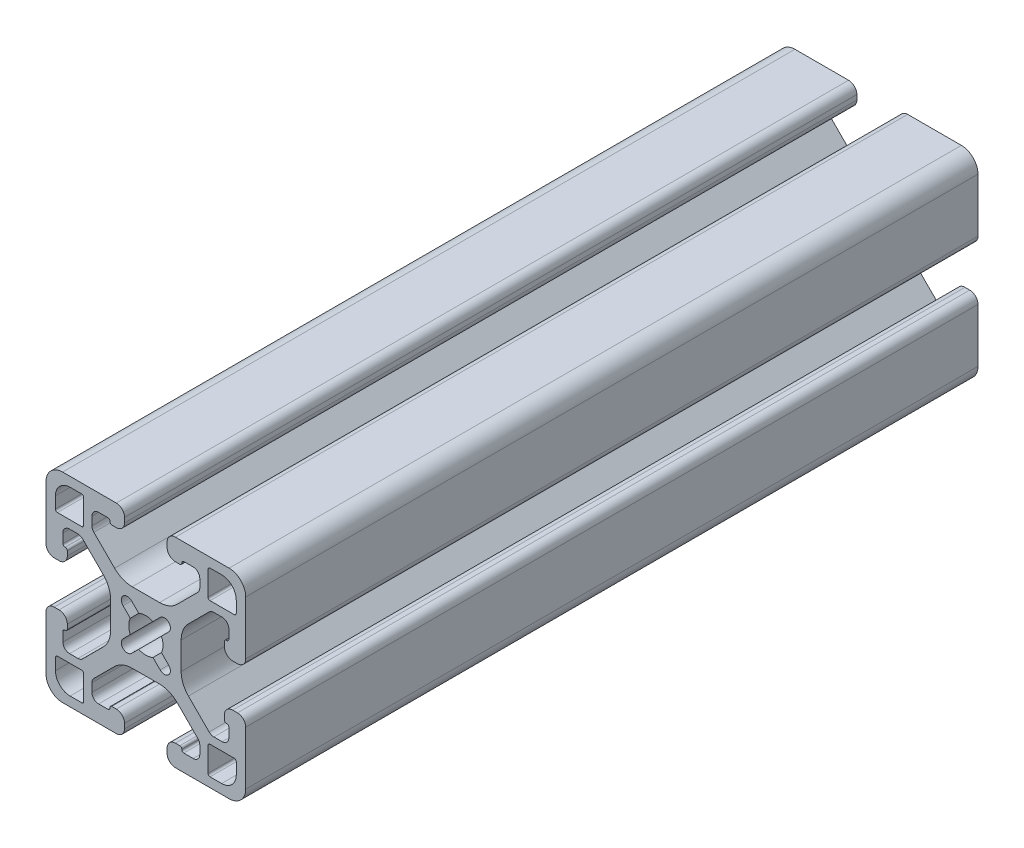
SolidWorks part; units mm, degrees
ref_plane "Front Plane" through (0, 0, 0) normal (0, 0, 1) x (1, 0, 0)
ref_plane "Top Plane" through (0, 0, 0) normal (0, 1, 0) x (1, 0, 0)
ref_plane "Right Plane" through (0, 0, 0) normal (1, 0, 0) x (0, 0, -1)
sketch "Sketch1" plane through (0, 0, 0) normal (0, 0, 1) x (1, 0, 0)
  line L0 (-66.7042, -2.4885) -> (-65.3338, -1.1181)
  line L1 (-65.3338, 1.5948) -> (-66.7042, 2.9652)
  line L2 (-65.0878, 4.5817) -> (-63.7174, 3.2113)
  line L3 (-61.0045, 3.2113) -> (-59.7212, 4.484)
  line L4 (-58.1153, 2.8781) -> (-59.3881, 1.5948)
  line L5 (-59.3881, -1.1181) -> (-58.0176, -2.4885)
  line L6 (-59.6341, -4.1049) -> (-61.0045, -2.7345)
  line L7 (-63.7174, -2.7345) -> (-65.0878, -4.1049)
  line L8 (-79.6075, 12.4812) -> (-79.6075, 14.691)
  line L9 (-76.8135, 17.485) -> (-74.6037, 17.485)
  line L10 (-74.2227, 17.104) -> (-74.2227, 12.4812)
  line L11 (-74.6037, 12.1002) -> (-79.2265, 12.1002)
  line L12 (-74.6037, -17.0082) -> (-76.8135, -17.0082)
  line L13 (-79.6075, -14.2142) -> (-79.6075, -12.0044)
  line L14 (-79.2265, -11.6234) -> (-74.6037, -11.6234)
  line L15 (-74.2227, -12.0044) -> (-74.2227, -16.6272)
  line L16 (-45.1143, -12.0044) -> (-45.1143, -14.2142)
  line L17 (-47.9083, -17.0082) -> (-50.1181, -17.0082)
  line L18 (-50.4991, -16.6272) -> (-50.4991, -12.0044)
  line L19 (-50.1181, -11.6234) -> (-45.4953, -11.6234)
  line L20 (-50.1181, 17.485) -> (-47.9083, 17.485)
  line L21 (-45.1143, 14.691) -> (-45.1143, 12.4812)
  line L22 (-45.4953, 12.1002) -> (-50.1181, 12.1002)
  line L23 (-50.4991, 12.4812) -> (-50.4991, 17.104)
  line L24 (-46.5368, -7.0006) -> (-46.5368, -8.7746)
  line L25 (-47.8067, -10.0486) -> (-49.3926, -10.0486)
  line L26 (-50.2907, -9.6767) -> (-54.2388, -5.7286)
  line L27 (-55.6299, -2.3699) -> (-55.6299, 2.8467)
  line L28 (-54.2388, 6.2053) -> (-50.2907, 10.1534)
  line L29 (-49.3926, 10.5254) -> (-47.8067, 10.5254)
  line L30 (-46.5368, 9.2513) -> (-46.5368, 7.4774)
  line L31 (-46.9178, 7.0964) -> (-46.994, 7.0964)
  line L32 (-47.375, 6.7154) -> (-47.3749, 5.8772)
  line L33 (-45.8001, 4.3024) -> (-44.8857, 4.3024)
  line L34 (-43.3109, 5.8772) -> (-43.3109, 16.1134)
  line L35 (-46.4859, 19.2884) -> (-56.7221, 19.2884)
  line L36 (-58.2969, 17.7136) -> (-58.2969, 16.7992)
  line L37 (-56.7222, 15.2244) -> (-55.884, 15.2244)
  line L38 (-55.503, 15.6054) -> (-55.503, 15.6816)
  line L39 (-55.122, 16.0626) -> (-53.348, 16.0626)
  line L40 (-52.0739, 14.7926) -> (-52.0739, 13.2067)
  line L41 (-52.4459, 12.3087) -> (-56.394, 8.3606)
  line L42 (-59.7526, 6.9694) -> (-64.9693, 6.9694)
  line L43 (-68.3279, 8.3606) -> (-72.276, 12.3087)
  line L44 (-72.6479, 13.2067) -> (-72.6479, 14.7926)
  line L45 (-71.3739, 16.0626) -> (-69.5999, 16.0626)
  line L46 (-69.2189, 15.6816) -> (-69.2189, 15.6054)
  line L47 (-68.8379, 15.2244) -> (-67.9997, 15.2244)
  line L48 (-66.4249, 16.7992) -> (-66.4249, 17.7136)
  line L49 (-67.9997, 19.2884) -> (-78.2359, 19.2884)
  line L50 (-81.4109, 16.1134) -> (-81.4109, 5.8772)
  line L51 (-79.8361, 4.3024) -> (-78.9217, 4.3024)
  line L52 (-77.3469, 5.8772) -> (-77.3469, 6.7154)
  line L53 (-77.7279, 7.0964) -> (-77.8041, 7.0964)
  line L54 (-78.1851, 7.4774) -> (-78.1851, 9.2513)
  line L55 (-76.9151, 10.5254) -> (-75.3293, 10.5254)
  line L56 (-74.4312, 10.1534) -> (-70.4831, 6.2053)
  line L57 (-69.0919, 2.8467) -> (-69.0919, -2.3699)
  line L58 (-70.4831, -5.7286) -> (-74.4312, -9.6767)
  line L59 (-75.3293, -10.0486) -> (-76.9151, -10.0486)
  line L60 (-78.1851, -8.7746) -> (-78.1851, -7.0006)
  line L61 (-77.8041, -6.6196) -> (-77.7279, -6.6196)
  line L62 (-77.3469, -6.2386) -> (-77.3469, -5.4004)
  line L63 (-78.9217, -3.8256) -> (-79.8361, -3.8256)
  line L64 (-81.4109, -5.4004) -> (-81.4109, -15.6366)
  line L65 (-78.2359, -18.8116) -> (-67.9997, -18.8116)
  line L66 (-66.4249, -17.2368) -> (-66.4249, -16.3224)
  line L67 (-67.9997, -14.7476) -> (-68.8379, -14.7476)
  line L68 (-69.2189, -15.1286) -> (-69.2189, -15.2048)
  line L69 (-69.5999, -15.5858) -> (-71.3739, -15.5858)
  line L70 (-72.6479, -14.3158) -> (-72.6479, -12.7299)
  line L71 (-72.276, -11.8319) -> (-68.3279, -7.8838)
  line L72 (-64.9693, -6.4926) -> (-59.7526, -6.4926)
  line L73 (-56.394, -7.8838) -> (-52.4459, -11.8319)
  line L74 (-52.0739, -12.7299) -> (-52.0739, -14.3158)
  line L75 (-53.348, -15.5858) -> (-55.122, -15.5858)
  line L76 (-55.503, -15.2048) -> (-55.503, -15.1286)
  line L77 (-55.884, -14.7476) -> (-56.7222, -14.7476)
  line L78 (-58.2969, -16.3224) -> (-58.2969, -17.2368)
  line L79 (-56.7221, -18.8116) -> (-46.4859, -18.8116)
  line L80 (-43.3109, -15.6366) -> (-43.3109, -5.4004)
  line L81 (-44.8857, -3.8256) -> (-45.8001, -3.8256)
  line L82 (-47.3749, -5.4004) -> (-47.375, -6.2386)
  line L83 (-46.994, -6.6196) -> (-46.9178, -6.6196)
  arc A0 (-66.7042, -2.4885) -> (-65.0878, -4.1049) centre (-65.896, -3.2967) ccw
  arc A1 (-65.3338, 1.5948) -> (-65.3338, -1.1181) centre (-62.3609, 0.2384) ccw
  arc A2 (-65.0878, 4.5817) -> (-66.7042, 2.9652) centre (-65.896, 3.7734) ccw
  arc A3 (-61.0045, 3.2113) -> (-63.7174, 3.2113) centre (-62.3609, 0.2384) ccw
  arc A4 (-58.1153, 2.8781) -> (-59.7212, 4.484) centre (-58.8259, 3.7734) ccw
  arc A5 (-59.3881, -1.1181) -> (-59.3881, 1.5948) centre (-62.3609, 0.2384) ccw
  arc A6 (-59.6341, -4.1049) -> (-58.0176, -2.4885) centre (-58.8259, -3.2967) ccw
  arc A7 (-63.7174, -2.7345) -> (-61.0045, -2.7345) centre (-62.3609, 0.2384) ccw
  arc A8 (-79.6075, 12.4812) -> (-79.2265, 12.1002) centre (-79.2265, 12.4812) ccw
  arc A9 (-76.8135, 17.485) -> (-79.6075, 14.691) centre (-76.8135, 14.691) ccw
  arc A10 (-74.2227, 17.104) -> (-74.6037, 17.485) centre (-74.6037, 17.104) ccw
  arc A11 (-74.6037, 12.1002) -> (-74.2227, 12.4812) centre (-74.6037, 12.4812) ccw
  arc A12 (-74.6037, -17.0082) -> (-74.2227, -16.6272) centre (-74.6037, -16.6272) ccw
  arc A13 (-79.6075, -14.2142) -> (-76.8135, -17.0082) centre (-76.8135, -14.2142) ccw
  arc A14 (-79.2265, -11.6234) -> (-79.6075, -12.0044) centre (-79.2265, -12.0044) ccw
  arc A15 (-74.2227, -12.0044) -> (-74.6037, -11.6234) centre (-74.6037, -12.0044) ccw
  arc A16 (-45.1143, -12.0044) -> (-45.4953, -11.6234) centre (-45.4953, -12.0044) ccw
  arc A17 (-47.9083, -17.0082) -> (-45.1143, -14.2142) centre (-47.9083, -14.2142) ccw
  arc A18 (-50.4991, -16.6272) -> (-50.1181, -17.0082) centre (-50.1181, -16.6272) ccw
  arc A19 (-50.1181, -11.6234) -> (-50.4991, -12.0044) centre (-50.1181, -12.0044) ccw
  arc A20 (-50.1181, 17.485) -> (-50.4991, 17.104) centre (-50.1181, 17.104) ccw
  arc A21 (-45.1143, 14.691) -> (-47.9083, 17.485) centre (-47.9083, 14.691) ccw
  arc A22 (-45.4953, 12.1002) -> (-45.1143, 12.4812) centre (-45.4953, 12.4812) ccw
  arc A23 (-50.4991, 12.4812) -> (-50.1181, 12.1002) centre (-50.1181, 12.4812) ccw
  arc A24 (-47.8067, -10.0486) -> (-46.5368, -8.7746) centre (-47.8067, -8.7786) ccw
  arc A25 (-50.2907, -9.6767) -> (-49.3926, -10.0486) centre (-49.3926, -8.7786) ccw
  arc A26 (-55.6299, -2.3699) -> (-54.2388, -5.7286) centre (-50.8801, -2.3699) ccw
  arc A27 (-54.2388, 6.2053) -> (-55.6299, 2.8467) centre (-50.8801, 2.8467) ccw
  arc A28 (-49.3926, 10.5254) -> (-50.2907, 10.1534) centre (-49.3926, 9.2554) ccw
  arc A29 (-46.5368, 9.2513) -> (-47.8067, 10.5254) centre (-47.8067, 9.2554) ccw
  arc A30 (-46.9178, 7.0964) -> (-46.5368, 7.4774) centre (-46.9178, 7.4774) ccw
  arc A31 (-46.994, 7.0964) -> (-47.375, 6.7154) centre (-46.994, 6.7154) ccw
  arc A32 (-47.3749, 5.8772) -> (-45.8001, 4.3024) centre (-45.8001, 5.8772) ccw
  arc A33 (-44.8857, 4.3024) -> (-43.3109, 5.8772) centre (-44.8857, 5.8772) ccw
  arc A34 (-43.3109, 16.1134) -> (-46.4859, 19.2884) centre (-46.4859, 16.1134) ccw
  arc A35 (-56.7221, 19.2884) -> (-58.2969, 17.7136) centre (-56.7221, 17.7136) ccw
  arc A36 (-58.2969, 16.7992) -> (-56.7222, 15.2244) centre (-56.7221, 16.7992) ccw
  arc A37 (-55.884, 15.2244) -> (-55.503, 15.6054) centre (-55.884, 15.6054) ccw
  arc A38 (-55.122, 16.0626) -> (-55.503, 15.6816) centre (-55.122, 15.6816) ccw
  arc A39 (-52.0739, 14.7926) -> (-53.348, 16.0626) centre (-53.3439, 14.7926) ccw
  arc A40 (-52.4459, 12.3087) -> (-52.0739, 13.2067) centre (-53.3439, 13.2067) ccw
  arc A41 (-59.7526, 6.9694) -> (-56.394, 8.3606) centre (-59.7526, 11.7192) ccw
  arc A42 (-68.3279, 8.3606) -> (-64.9693, 6.9694) centre (-64.9693, 11.7192) ccw
  arc A43 (-72.6479, 13.2067) -> (-72.276, 12.3087) centre (-71.3779, 13.2067) ccw
  arc A44 (-71.3739, 16.0626) -> (-72.6479, 14.7926) centre (-71.3779, 14.7926) ccw
  arc A45 (-69.2189, 15.6816) -> (-69.5999, 16.0626) centre (-69.5999, 15.6816) ccw
  arc A46 (-69.2189, 15.6054) -> (-68.8379, 15.2244) centre (-68.8379, 15.6054) ccw
  arc A47 (-67.9997, 15.2244) -> (-66.4249, 16.7992) centre (-67.9997, 16.7992) ccw
  arc A48 (-66.4249, 17.7136) -> (-67.9997, 19.2884) centre (-67.9997, 17.7136) ccw
  arc A49 (-78.2359, 19.2884) -> (-81.4109, 16.1134) centre (-78.2359, 16.1134) ccw
  arc A50 (-81.4109, 5.8772) -> (-79.8361, 4.3024) centre (-79.8361, 5.8772) ccw
  arc A51 (-78.9217, 4.3024) -> (-77.3469, 5.8772) centre (-78.9217, 5.8772) ccw
  arc A52 (-77.3469, 6.7154) -> (-77.7279, 7.0964) centre (-77.7279, 6.7154) ccw
  arc A53 (-78.1851, 7.4774) -> (-77.8041, 7.0964) centre (-77.8041, 7.4774) ccw
  arc A54 (-76.9151, 10.5254) -> (-78.1851, 9.2513) centre (-76.9151, 9.2554) ccw
  arc A55 (-74.4312, 10.1534) -> (-75.3293, 10.5254) centre (-75.3293, 9.2554) ccw
  arc A56 (-69.0919, 2.8467) -> (-70.4831, 6.2053) centre (-73.8417, 2.8467) ccw
  arc A57 (-70.4831, -5.7286) -> (-69.0919, -2.3699) centre (-73.8417, -2.3699) ccw
  arc A58 (-75.3293, -10.0486) -> (-74.4312, -9.6767) centre (-75.3293, -8.7786) ccw
  arc A59 (-78.1851, -8.7746) -> (-76.9151, -10.0486) centre (-76.9151, -8.7786) ccw
  arc A60 (-77.8041, -6.6196) -> (-78.1851, -7.0006) centre (-77.8041, -7.0006) ccw
  arc A61 (-77.7279, -6.6196) -> (-77.3469, -6.2386) centre (-77.7279, -6.2386) ccw
  arc A62 (-77.3469, -5.4004) -> (-78.9217, -3.8256) centre (-78.9217, -5.4004) ccw
  arc A63 (-79.8361, -3.8256) -> (-81.4109, -5.4004) centre (-79.8361, -5.4004) ccw
  arc A64 (-81.4109, -15.6366) -> (-78.2359, -18.8116) centre (-78.2359, -15.6366) ccw
  arc A65 (-67.9997, -18.8116) -> (-66.4249, -17.2368) centre (-67.9997, -17.2368) ccw
  arc A66 (-66.4249, -16.3224) -> (-67.9997, -14.7476) centre (-67.9997, -16.3224) ccw
  arc A67 (-68.8379, -14.7476) -> (-69.2189, -15.1286) centre (-68.8379, -15.1286) ccw
  arc A68 (-69.5999, -15.5858) -> (-69.2189, -15.2048) centre (-69.5999, -15.2048) ccw
  arc A69 (-72.6479, -14.3158) -> (-71.3739, -15.5858) centre (-71.3779, -14.3158) ccw
  arc A70 (-72.276, -11.8319) -> (-72.6479, -12.7299) centre (-71.3779, -12.7299) ccw
  arc A71 (-64.9693, -6.4926) -> (-68.3279, -7.8838) centre (-64.9693, -11.2424) ccw
  arc A72 (-56.394, -7.8838) -> (-59.7526, -6.4926) centre (-59.7526, -11.2424) ccw
  arc A73 (-52.0739, -12.7299) -> (-52.4459, -11.8319) centre (-53.3439, -12.7299) ccw
  arc A74 (-53.348, -15.5858) -> (-52.0739, -14.3158) centre (-53.3439, -14.3158) ccw
  arc A75 (-55.503, -15.2048) -> (-55.122, -15.5858) centre (-55.122, -15.2048) ccw
  arc A76 (-55.503, -15.1286) -> (-55.884, -14.7476) centre (-55.884, -15.1286) ccw
  arc A77 (-56.7222, -14.7476) -> (-58.2969, -16.3224) centre (-56.7221, -16.3224) ccw
  arc A78 (-58.2969, -17.2368) -> (-56.7221, -18.8116) centre (-56.7221, -17.2368) ccw
  arc A79 (-46.4859, -18.8116) -> (-43.3109, -15.6366) centre (-46.4859, -15.6366) ccw
  arc A80 (-43.3109, -5.4004) -> (-44.8857, -3.8256) centre (-44.8857, -5.4004) ccw
  arc A81 (-45.8001, -3.8256) -> (-47.3749, -5.4004) centre (-45.8001, -5.4004) ccw
  arc A82 (-47.375, -6.2386) -> (-46.994, -6.6196) centre (-46.994, -6.2386) ccw
  arc A83 (-46.5368, -7.0006) -> (-46.9178, -6.6196) centre (-46.9178, -7.0006) ccw
extrude "Extrude1" add sketch "Sketch1" against normal blind 139.7
